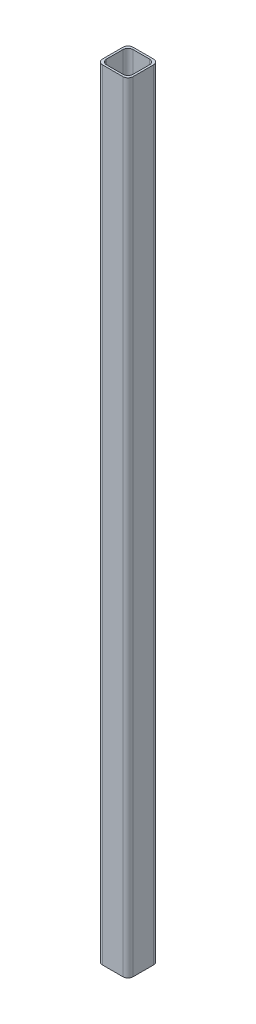
SolidWorks part; units mm, degrees
ref_plane "Спереди" through (0, 0, 0) normal (0, 0, 1) x (1, 0, 0)
ref_plane "Сверху" through (0, 0, 0) normal (0, 1, 0) x (1, 0, 0)
ref_plane "Справа" through (0, 0, 0) normal (1, 0, 0) x (0, 0, -1)
sketch "Эскиз1" plane through (0, 0, 0) normal (0, 1, 0) x (1, 0, 0)
  line L1 (-20, 30) -> (20, 30)
  line L2 (-30, 20) -> (-30, -20)
  line L3 (-20, -30) -> (20, -30)
  line L4 (30, 20) -> (30, -20)
  line L5 (-30, 30) -> (30, -30) construction
  line L6 (-30, -30) -> (30, 30) construction
  line L7 (-16, 26) -> (16, 26)
  line L8 (-26, 16) -> (-26, -16)
  line L9 (-16, -26) -> (16, -26)
  line L10 (26, 16) -> (26, -16)
  line L11 (-26, 26) -> (26, -26) construction
  line L12 (-26, -26) -> (26, 26) construction
  arc A0 (20, 30) -> (30, 20) centre (20, 20) cw
  arc A1 (-20, 30) -> (-30, 20) centre (-20, 20) ccw
  arc A2 (-30, -20) -> (-20, -30) centre (-20, -20) ccw
  arc A3 (20, -30) -> (30, -20) centre (20, -20) ccw
  arc A4 (16, -26) -> (26, -16) centre (16, -16) ccw
  arc A5 (16, 26) -> (26, 16) centre (16, 16) cw
  arc A6 (-16, 26) -> (-26, 16) centre (-16, 16) ccw
  arc A7 (-26, -16) -> (-16, -26) centre (-16, -16) ccw
  point P0 (0, 0)
  point P6 (0, 0)
  dimension "D5" = 10
  dimension "D1" = 60
  dimension "D2" = 60
  dimension "D3" = 4
  dimension "D4" = 4
extrude "Бобышка-Вытянуть1" add sketch "Эскиз1" along normal blind 1530
